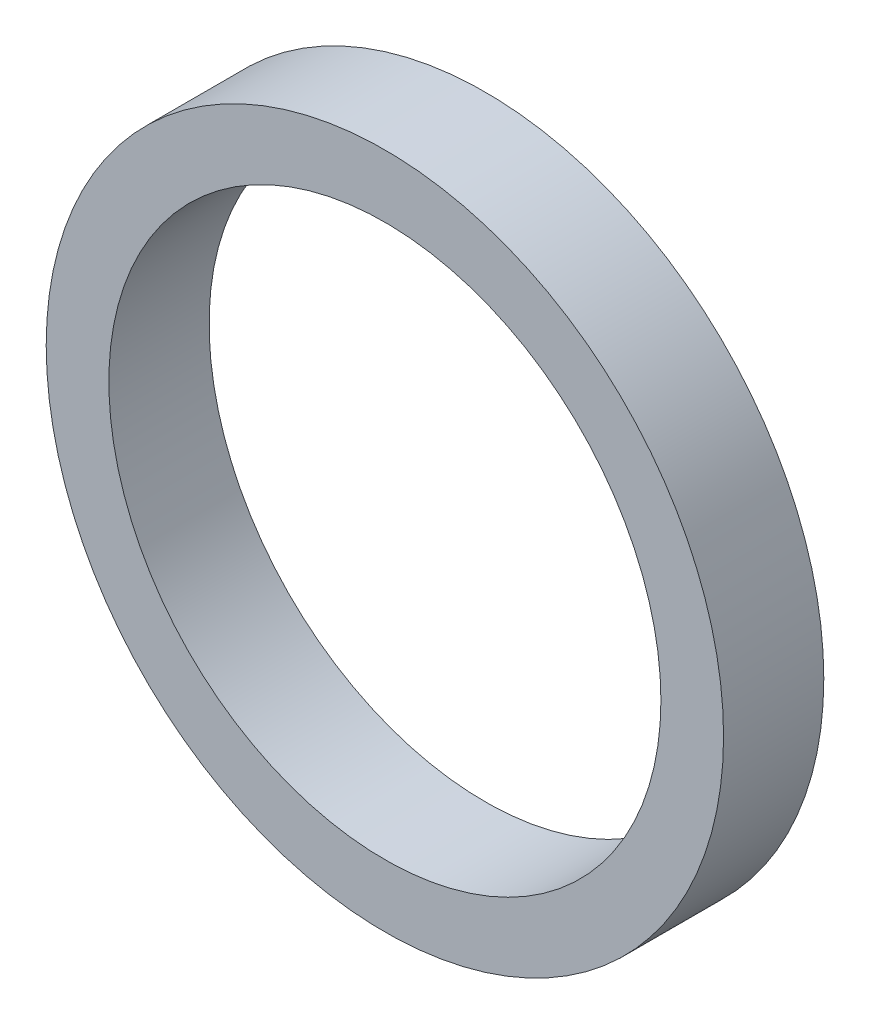
SolidWorks part; units mm, degrees
ref_plane "Front Plane" through (0, 0, 0) normal (0, 0, 1) x (1, 0, 0)
ref_plane "Top Plane" through (0, 0, 0) normal (0, 1, 0) x (1, 0, 0)
ref_plane "Right Plane" through (0, 0, 0) normal (1, 0, 0) x (0, 0, -1)
sketch "Sketch3" plane through (0, 0, 0) normal (0, 0, 1) x (1, 0, 0)
  circle A0 centre (0, 0) radius 13.515
  circle A2 centre (0, 0) radius 11.015
  dimension "D1" = 27.03
  dimension "D2" = 22.03
extrude "Boss-Extrude3" add sketch "Sketch3" along normal blind 4
equation "\"InnerWall\"= 22.03"
equation "\"OuterWall\" = \"InnerWall\" + 5"
equation "\"Depth\"= 4"
equation "\"D1@Sketch3\"=\"OuterWall\""
equation "\"D2@Sketch3\"=\"InnerWall\""
equation "\"D1@Boss-Extrude3\"=\"Depth\""
